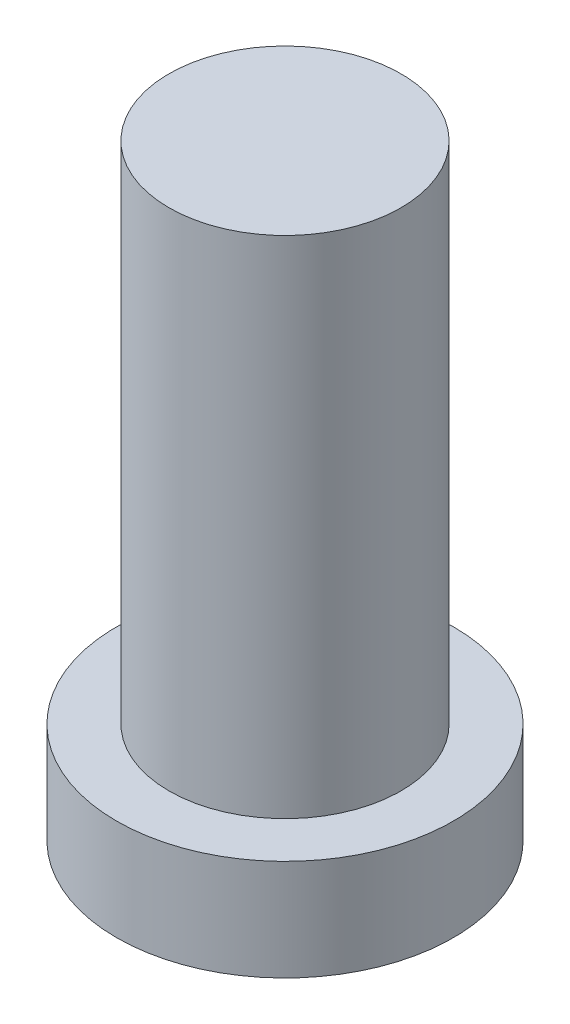
SolidWorks part; units mm, degrees
ref_plane "Front Plane" through (0, 0, 0) normal (0, 0, 1) x (1, 0, 0)
ref_plane "Top Plane" through (0, 0, 0) normal (0, 1, 0) x (1, 0, 0)
ref_plane "Right Plane" through (0, 0, 0) normal (1, 0, 0) x (0, 0, -1)
sketch "Sketch1" plane through (0, 0, 0) normal (0, 1, 0) x (1, 0, 0)
  circle A0 centre (0, 0) radius 50
  dimension "D1" = 100
extrude "Boss-Extrude1" add sketch "Sketch1" along normal blind 30
sketch "Sketch2" plane through (0, 30, 0) normal (0, 1, 0) x (1, 0, 0)
  circle A0 centre (0, 0) radius 34.466
extrude "Boss-Extrude2" add sketch "Sketch2" along normal blind 150
